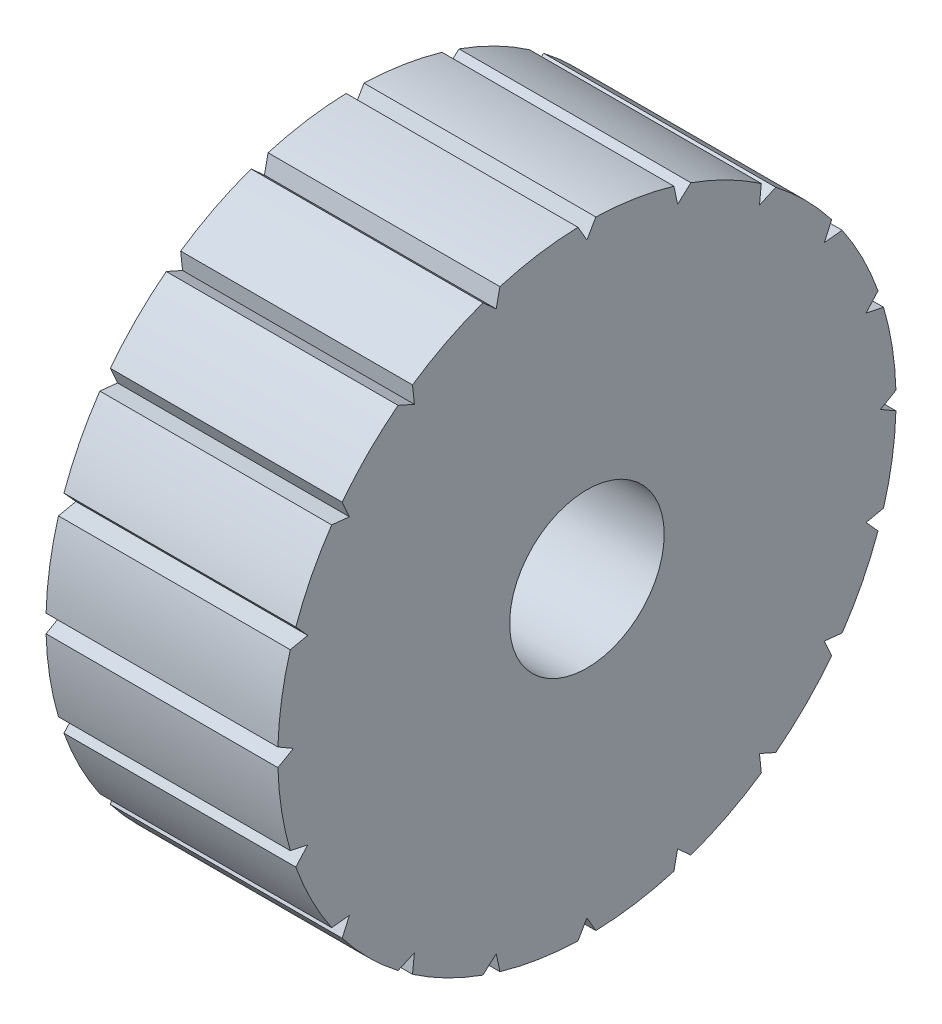
SolidWorks part; units mm, degrees
ref_plane "Front Plane" through (0, 0, 0) normal (0, 0, 1) x (1, 0, 0)
ref_plane "Top Plane" through (0, 0, 0) normal (0, 1, 0) x (1, 0, 0)
ref_plane "Right Plane" through (0, 0, 0) normal (1, 0, 0) x (0, 0, -1)
sketch "Sketch1" plane through (0, 0, 0) normal (1, 0, 0) x (0, 0, -1)
  circle A0 centre (0, 0) radius 100
  circle A1 centre (0, 0) radius 25
  dimension "D1" = 200
  dimension "D2" = 50
extrude "Boss-Extrude1" add sketch "Sketch1" along normal blind 75
sketch "Sketch2" plane through (75, 0, 0) normal (1, 0, 0) x (0, 0, -1)
  line L0 (0, 0) -> (0, 100) construction
  line L1 (2.8868, 99.9583) -> (0, 94.9583)
  line L2 (-2.8868, 99.9583) -> (0, 94.9583)
  circle A0 centre (0, 0) radius 100 construction
  arc A1 (2.8868, 99.9583) -> (-2.8868, 99.9583) centre (0, 0) ccw
  dimension "D1" = 30
  dimension "D2" = 5
extrude "Cut-Extrude1" cut sketch "Sketch2" against normal through all
pattern_circular "CirPattern1" count 20 over 360 about axis through (0, 0, 0) along (1, 0, 0) of "Cut-Extrude1"
